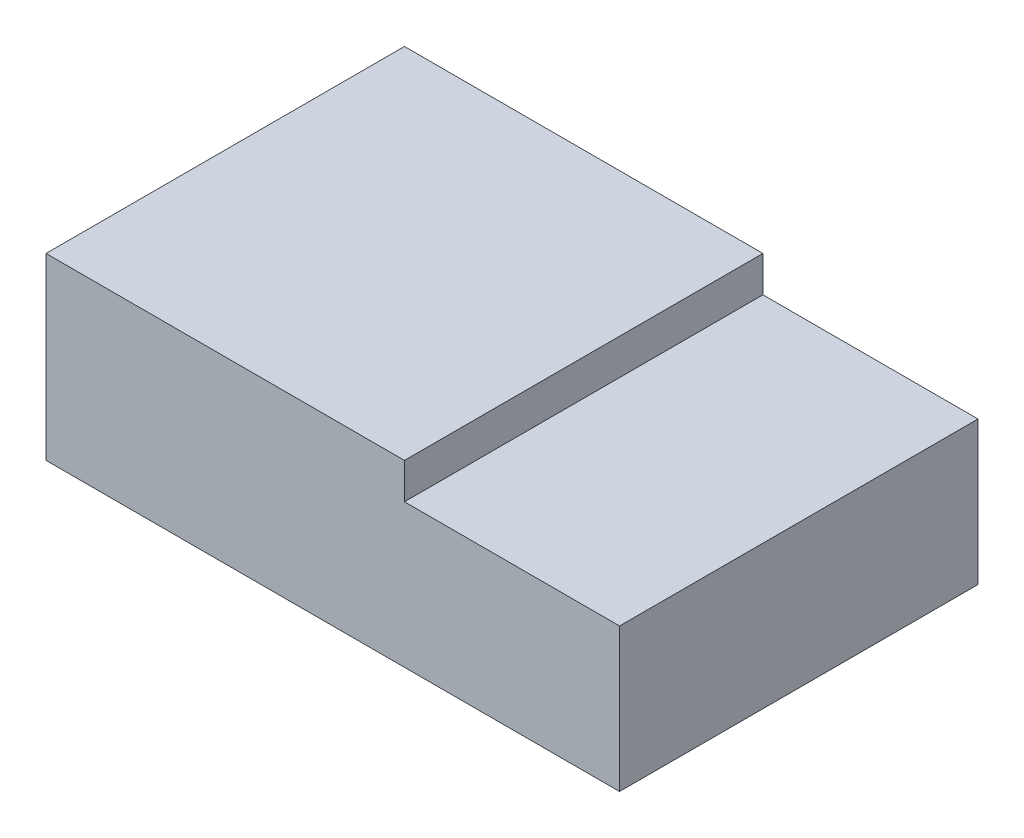
SolidWorks part; units mm, degrees
ref_plane "Front Plane" through (0, 0, 0) normal (0, 0, 1) x (1, 0, 0)
ref_plane "Top Plane" through (0, 0, 0) normal (0, 1, 0) x (1, 0, 0)
ref_plane "Right Plane" through (0, 0, 0) normal (1, 0, 0) x (0, 0, -1)
sketch "Sketch1" plane through (0, 0, 0) normal (0, 0, 1) x (1, 0, 0)
  line L0 (0, 0) -> (101.6, 0)
  line L1 (101.6, 0) -> (101.6, 25.4)
  line L2 (101.6, 25.4) -> (63.5, 25.4)
  line L3 (63.5, 25.4) -> (63.5, 31.75)
  line L4 (63.5, 31.75) -> (0, 31.75)
  line L5 (0, 31.75) -> (0, 0)
  dimension "D1" = 101.6
  dimension "D2" = 25.4
  dimension "D3" = 38.1
  dimension "D4" = 31.75
extrude "Boss-Extrude1" add sketch "Sketch1" along normal blind 63.5 contours L4 L5 L0 L1 L2 L3
